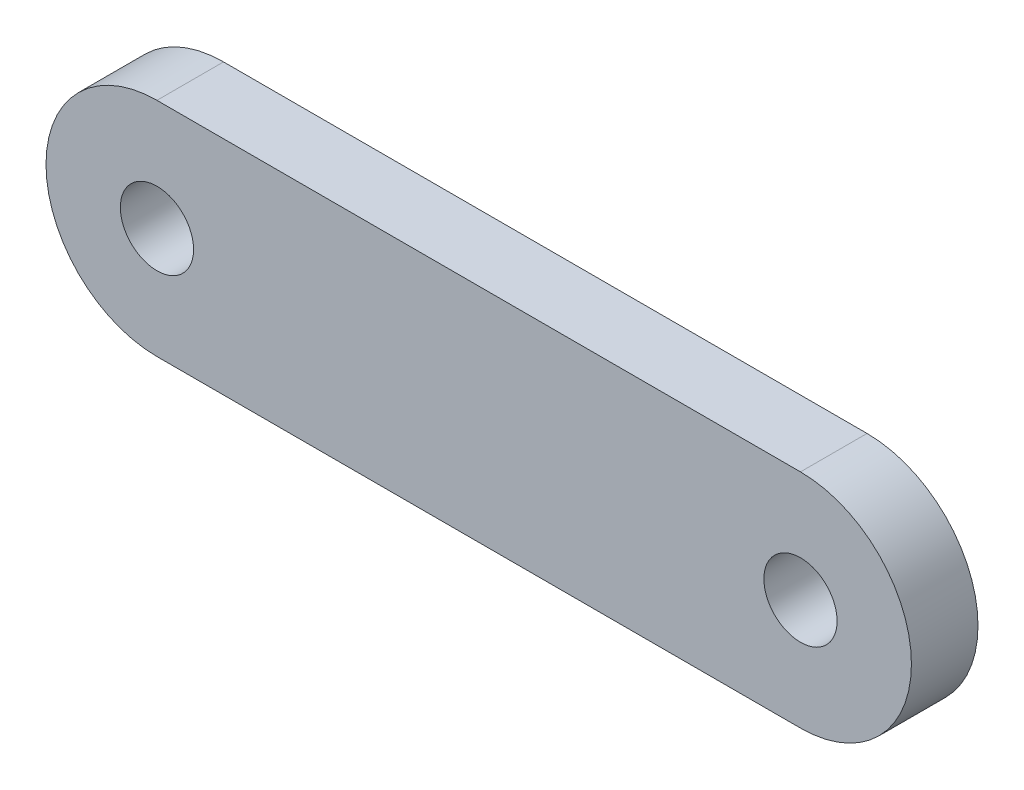
SolidWorks part; units mm, degrees
ref_plane "前视基准面" through (0, 0, 0) normal (0, 0, 1) x (1, 0, 0)
ref_plane "上视基准面" through (0, 0, 0) normal (0, 1, 0) x (1, 0, 0)
ref_plane "右视基准面" through (0, 0, 0) normal (1, 0, 0) x (0, 0, -1)
sketch "草图1" plane through (0, 0, 0) normal (0, 0, 1) x (1, 0, 0)
  line L0 (0, 0) -> (29, 0)
  line L1 (0, -10) -> (29, -10)
  arc A0 (0, 0) -> (0, -10) centre (0, -5) ccw
  arc A1 (29, 0) -> (29, -10) centre (29, -5) cw
  circle A2 centre (0, -5) radius 1.65
  circle A3 centre (29, -5) radius 1.65
  dimension "D2" = 29
  dimension "D3" = 3.3
  dimension "D1" = 10
extrude "凸台-拉伸1" add sketch "草图1" along normal blind 3
